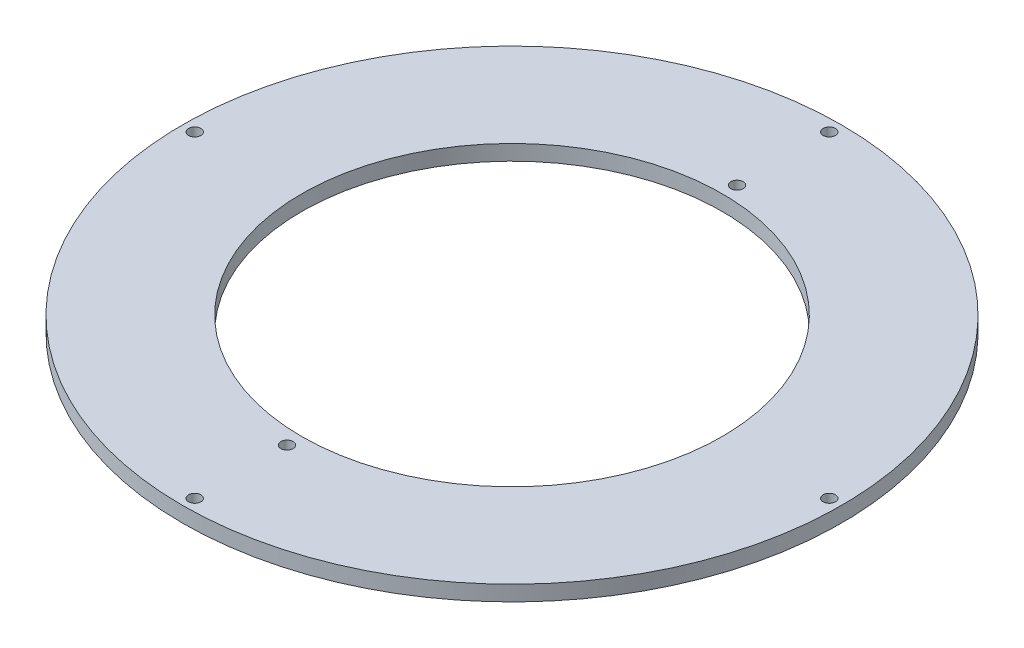
SolidWorks part; units mm, degrees
ref_plane "Front Plane" through (0, 0, 0) normal (0, 0, 1) x (1, 0, 0)
ref_plane "Top Plane" through (0, 0, 0) normal (0, 1, 0) x (1, 0, 0)
ref_plane "Right Plane" through (0, 0, 0) normal (1, 0, 0) x (0, 0, -1)
sketch "Sketch1" plane through (0, 0, 0) normal (0, 1, 0) x (1, 0, 0)
  circle A0 centre (0, 0) radius 67
  circle A1 centre (0, 0) radius 42.75
  circle A2 centre (0, 0) radius 67 construction
  circle A3 centre (0, 0) radius 67 construction
  circle A4 centre (0, 0) radius 42.75 construction
  circle A8 centre (0, 0) radius 42.75 construction
  circle A9 centre (0, 0) radius 23.5 construction
  circle A10 centre (0, 0) radius 23.5 construction
  dimension "D3" = 85.5
  dimension "D1" = 47
  dimension "D2" = 85.5
extrude "Boss-Extrude1" add sketch "Sketch1" along normal blind 3.125
sketch "Sketch2" plane through (0, 3.125, 0) normal (0, 1, 0) x (1, 0, 0)
  circle A0 centre (0, 64.5) radius 1.5 construction
  circle A1 centre (64.5, 0) radius 1.5 construction
  circle A2 centre (-64.5, 0) radius 1.5 construction
  circle A3 centre (0, -64.5) radius 1.5 construction
  circle A4 centre (0, 64.5) radius 1.5 construction
  circle A5 centre (64.5, 0) radius 1.5 construction
  circle A6 centre (-64.5, 0) radius 1.5 construction
  circle A7 centre (0, -64.5) radius 1.5 construction
  circle A8 centre (64.5, 0) radius 1.25
  circle A9 centre (0, 64.5) radius 1.25
  circle A10 centre (-64.5, 0) radius 1.25
  circle A11 centre (0, -64.5) radius 1.25
  dimension "D1" = 2.5
extrude "Cut-Extrude1" cut sketch "Sketch2" against normal through all
sketch "Sketch3" plane through (0, 3.125, 0) normal (0, 1, 0) x (1, 0, 0)
  line L0 (0, 0) -> (41.5657, 0) construction
  circle A0 centre (0, 0) radius 45.75 construction
  circle A1 centre (0, 0) radius 42.75 construction
  circle A2 centre (0, 45.75) radius 1.25
  circle A3 centre (0, -45.75) radius 1.25
  dimension "D1" = 3
  dimension "D2" = 2.5
extrude "Cut-Extrude2" cut sketch "Sketch3" against normal through all
equation "\"D2@Sketch1\"    = \"D3@Sketch1\""
